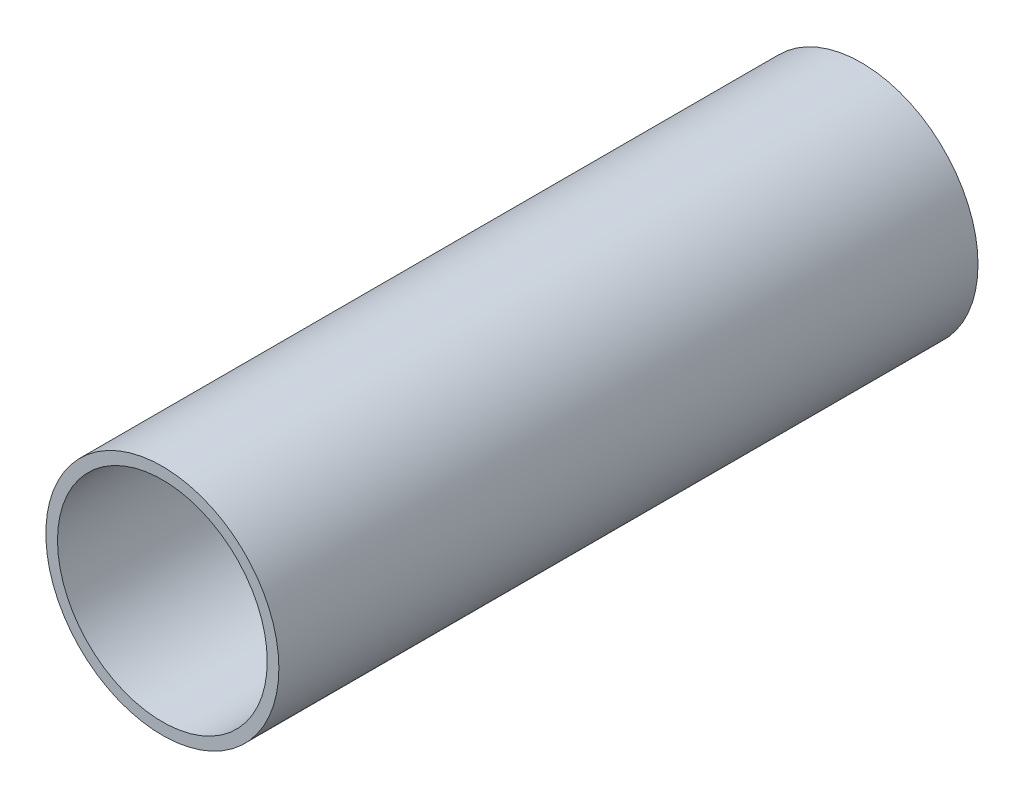
SolidWorks part; units mm, degrees
ref_plane "Front" through (0, 0, 0) normal (0, 0, 1) x (1, 0, 0)
ref_plane "Top" through (0, 0, 0) normal (0, 1, 0) x (1, 0, 0)
ref_plane "Right" through (0, 0, 0) normal (1, 0, 0) x (0, 0, -1)
sketch "Sketch1" plane through (0, 0, 0) normal (0, 0, 1) x (1, 0, 0)
  circle A0 centre (0, 0) radius 10
  circle A1 centre (0, 0) radius 9
  dimension "D1" = 20
  dimension "D2" = 18
extrude "Boss-Extrude1" add sketch "Sketch1" along normal blind 60
